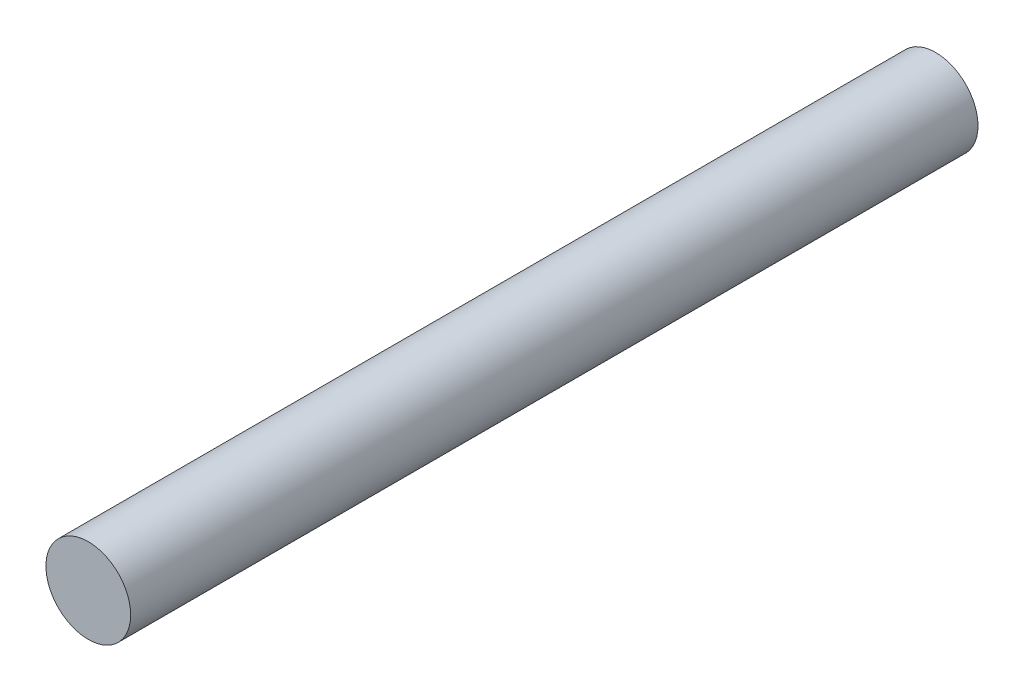
SolidWorks part; units mm, degrees
ref_plane "Front Plane" through (0, 0, 0) normal (0, 0, 1) x (1, 0, 0)
ref_plane "Top Plane" through (0, 0, 0) normal (0, 1, 0) x (1, 0, 0)
ref_plane "Right Plane" through (0, 0, 0) normal (1, 0, 0) x (0, 0, -1)
sketch "Sketch1" plane through (0, 0, 0) normal (0, 0, 1) x (1, 0, 0)
  circle A0 centre (0, 0) radius 1
extrude "Boss-Extrude1" add sketch "Sketch1" along normal blind 20
